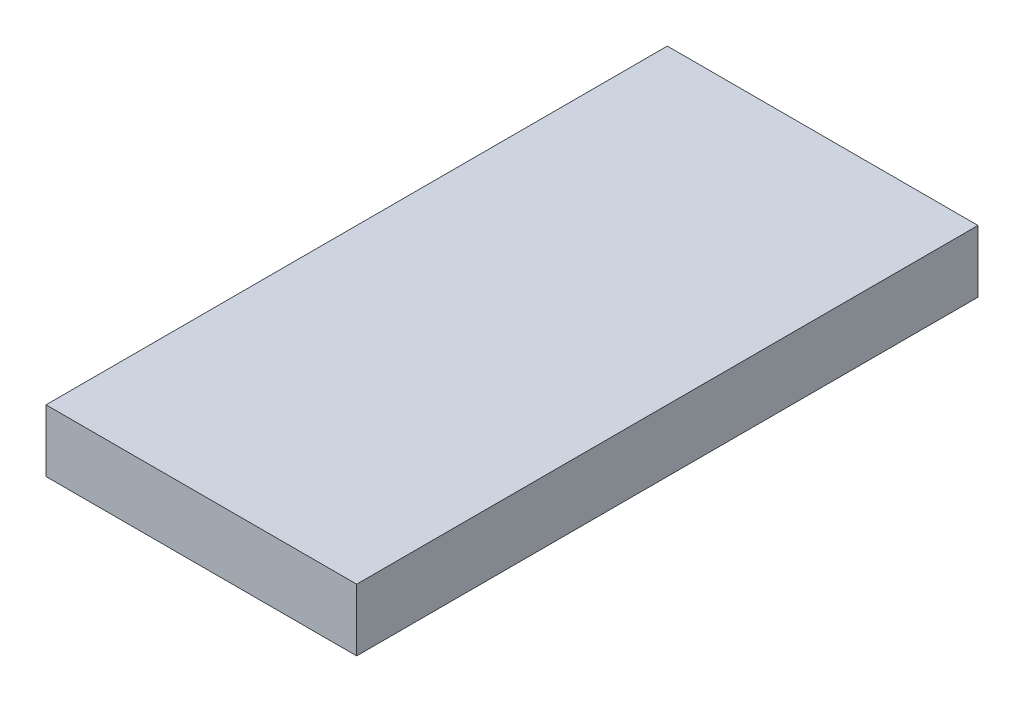
SolidWorks part; units mm, degrees
ref_plane "前基準面" through (0, 0, 0) normal (0, 0, 1) x (1, 0, 0)
ref_plane "上基準面" through (0, 0, 0) normal (0, 1, 0) x (1, 0, 0)
ref_plane "右基準面" through (0, 0, 0) normal (1, 0, 0) x (0, 0, -1)
ref_plane "平面1"
sketch "草圖1" plane through (0, 0, 0) normal (0, 1, 0) x (-1, 0, 0)
  line L0 (30, -60) -> (-30, -60)
  line L1 (-30, -60) -> (-30, 60)
  line L2 (-30, 60) -> (30, 60)
  line L3 (30, 60) -> (30, -60)
  dimension "D1" = 60
  dimension "D2" = 120
extrude "擠出1" add sketch "草圖1" along normal blind 12
